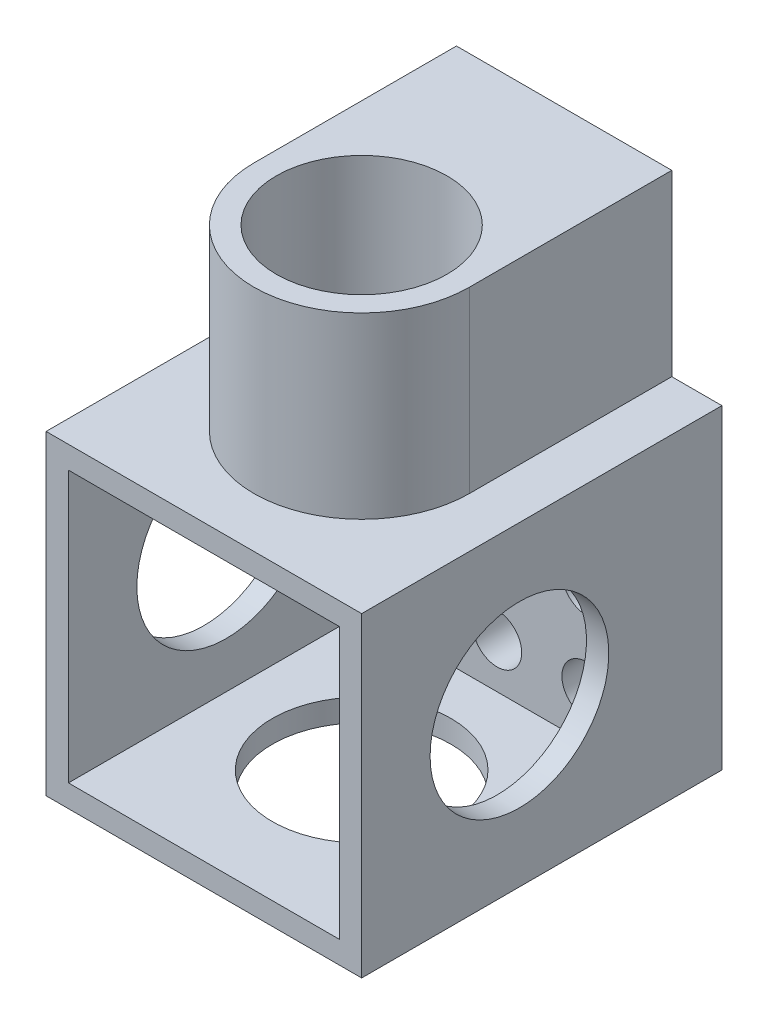
SolidWorks part; units mm, degrees
ref_plane "Front Plane" through (0, 0, 0) normal (0, 0, 1) x (1, 0, 0)
ref_plane "Top Plane" through (0, 0, 0) normal (0, 1, 0) x (1, 0, 0)
ref_plane "Right Plane" through (0, 0, 0) normal (1, 0, 0) x (0, 0, -1)
sketch "Sketch1" plane through (0, 0, 0) normal (0, 1, 0) x (1, 0, 0)
  line L1 (-19.25, -19.25) -> (19.25, -19.25)
  line L2 (-19.25, -19.25) -> (-19.25, 19.25)
  line L3 (-19.25, 19.25) -> (19.25, 19.25)
  line L4 (19.25, -19.25) -> (19.25, 19.25)
  line L5 (-19.25, -19.25) -> (19.25, 19.25) construction
  line L6 (-19.25, 19.25) -> (19.25, -19.25) construction
  line L7 (-22.425, -22.425) -> (22.425, -22.425)
  line L8 (-22.425, -22.425) -> (-22.425, 22.425)
  line L9 (-22.425, 22.425) -> (22.425, 22.425)
  line L10 (22.425, -22.425) -> (22.425, 22.425)
  line L11 (-22.425, -22.425) -> (22.425, 22.425) construction
  line L12 (-22.425, 22.425) -> (22.425, -22.425) construction
  point P0 (0, 0)
  point P6 (0, 0)
  dimension "D1" = 38.5
  dimension "D2" = 38.5
  dimension "D3" = 3.175
  dimension "D4" = 3.175
extrude "Boss-Extrude1" add sketch "Sketch1" along normal mid plane 38.5
sketch "Sketch2" plane through (0, 19.25, 0) normal (0, 1, 0) x (1, 0, 0)
  line L1 (-22.425, 22.425) -> (22.425, 22.425)
  line L2 (-22.425, 22.425) -> (-22.425, -22.425)
  line L3 (-22.425, -22.425) -> (22.425, -22.425)
  line L4 (22.425, 22.425) -> (22.425, -22.425)
extrude "Boss-Extrude2" add sketch "Sketch2" along normal blind 3.175
sketch "Sketch3" plane through (0, -19.25, 0) normal (0, -1, 0) x (1, 0, 0)
  line L1 (22.425, -22.425) -> (-22.425, -22.425)
  line L2 (22.425, -22.425) -> (22.425, 22.425)
  line L3 (22.425, 22.425) -> (-22.425, 22.425)
  line L4 (-22.425, -22.425) -> (-22.425, 22.425)
extrude "Boss-Extrude3" add sketch "Sketch3" along normal blind 3.175
sketch "Sketch5" plane through (0, -22.425, -22.425) normal (0, 1, 0) x (1, 0, 0)
  circle A0 centre (0, -22.425) radius 12.7
  dimension "D1" = 25.4
extrude "Cut-Extrude1" cut sketch "Sketch5" along normal up to next (3.175 mm away) from surface at 0 starting at face at (0, -22.425, 0)
sketch "Sketch6" plane through (0, 0, 0) normal (0, 1, 0) x (1, 0, 0)
  circle A0 centre (0, 0) radius 10
  dimension "D1" = 20
extrude "Cut-Extrude2" cut sketch "Sketch6" against normal up to next (19.25 mm away) from surface at 22.425 starting at face at (0, 22.425, 0)
sketch "Sketch7" plane through (-22.425, 0, 0) normal (-1, 0, 0) x (0, 0, 1)
  circle A0 centre (0, 0) radius 12.7
  dimension "D1" = 25.4
extrude "Cut-Extrude3" cut sketch "Sketch7" against normal through all from surface at 0 starting at face at (-22.425, 0, 0)
sketch "Sketch8" plane through (0, 0, -22.425) normal (0, 0, -1) x (-1, 0, 0)
  line L0 (-12.7, 12.7) -> (0, 12.7) construction
  line L1 (-22.425, -22.425) -> (22.425, -22.425)
  line L2 (-22.425, 22.425) -> (-22.425, -22.425)
  line L3 (-22.425, 22.425) -> (22.425, 22.425)
  line L4 (22.425, -22.425) -> (22.425, 22.425)
  circle A0 centre (-12.7, 12.7) radius 2.2225
  circle A1 centre (0, 12.7) radius 2.2225
  circle A2 centre (12.7, 12.7) radius 2.2225
  circle A3 centre (0, 0) radius 2.2225
  circle A4 centre (12.7, 0) radius 2.2225
  circle A5 centre (0, -12.7) radius 2.2225
  circle A6 centre (12.7, -12.7) radius 2.2225
  circle A7 centre (-12.7, 0) radius 2.2225
  circle A8 centre (-12.7, -12.7) radius 2.2225
  dimension "D1" = 4.445
  dimension "D2" = 12.7
  dimension "D3" = 12.7
  dimension "D6" = 12.7
  dimension "D4" = 3
  dimension "D5" = 3
extrude "Boss-Extrude4" add sketch "Sketch8" along normal blind 6.35
sketch "Sketch9" plane through (0, 0, -19.25) normal (0, 0, 1) x (1, 0, 0)
  line L0 (12.7, 12.7) -> (0, 12.7) construction
  circle A0 centre (12.7, 12.7) radius 3.4925
  circle A1 centre (0, 12.7) radius 3.4925
  circle A2 centre (-12.7, 12.7) radius 3.4925
  circle A3 centre (0, 0) radius 3.4925
  circle A4 centre (-12.7, 0) radius 3.4925
  circle A5 centre (0, -12.7) radius 3.4925
  circle A6 centre (-12.7, -12.7) radius 3.4925
  circle A7 centre (12.7, 0) radius 3.4925
  circle A8 centre (12.7, -12.7) radius 3.4925
  dimension "D1" = 6.985
  dimension "D4" = 12.7
  dimension "D2" = 3
  dimension "D3" = 3
extrude "Cut-Extrude4" cut sketch "Sketch9" against normal blind 6.35
sketch "Sketch10" plane through (0, 0, 22.425) normal (0, 0, 1) x (1, 0, 0)
  line L0 (-22.425, 22.425) -> (-22.425, -22.425) construction
  line L1 (-19.25, -19.25) -> (19.25, -19.25)
  line L2 (-19.25, -19.25) -> (-19.25, 19.25)
  line L3 (-19.25, 19.25) -> (19.25, 19.25)
  line L4 (19.25, -19.25) -> (19.25, 19.25)
  line L5 (-19.25, -19.25) -> (19.25, 19.25) construction
  line L6 (-19.25, 19.25) -> (19.25, -19.25) construction
  line L7 (-22.425, 22.425) -> (22.425, 22.425) construction
  point P0 (0, 0)
  dimension "D1" = 3.175
  dimension "D2" = 3.175
extrude "Cut-Extrude5" cut sketch "Sketch10" against normal up to next
sketch "Sketch11" plane through (0, 22.425, 0) normal (0, 1, 0) x (1, 0, 0)
  line L2 (-15.3035, 0) -> (-15.3035, 28.775)
  line L3 (-15.3035, 28.775) -> (15.3035, 28.775)
  line L4 (15.3035, 0) -> (15.3035, 28.775)
  line L5 (-22.425, 28.775) -> (22.425, 28.775) construction
  circle A0 centre (0, 0) radius 12.1285
  arc A1 (-15.3035, 0) -> (15.3035, 0) centre (0, 0) ccw
  point P7 (15.7163, 0)
  point P8 (15.7163, 0)
  point P9 (0, 0)
  point P10 (-15.7163, 22.6131)
  point P11 (0, -12.1285)
  point P12 (0, -15.3035)
  point P13 (-15.3035, 0)
  point P14 (15.3035, 0)
  point P17 (22.425, 6.3279)
  dimension "D1" = 24.257
  dimension "D2" = 3.175
extrude "Boss-Extrude5" add sketch "Sketch11" along normal blind 25.4
